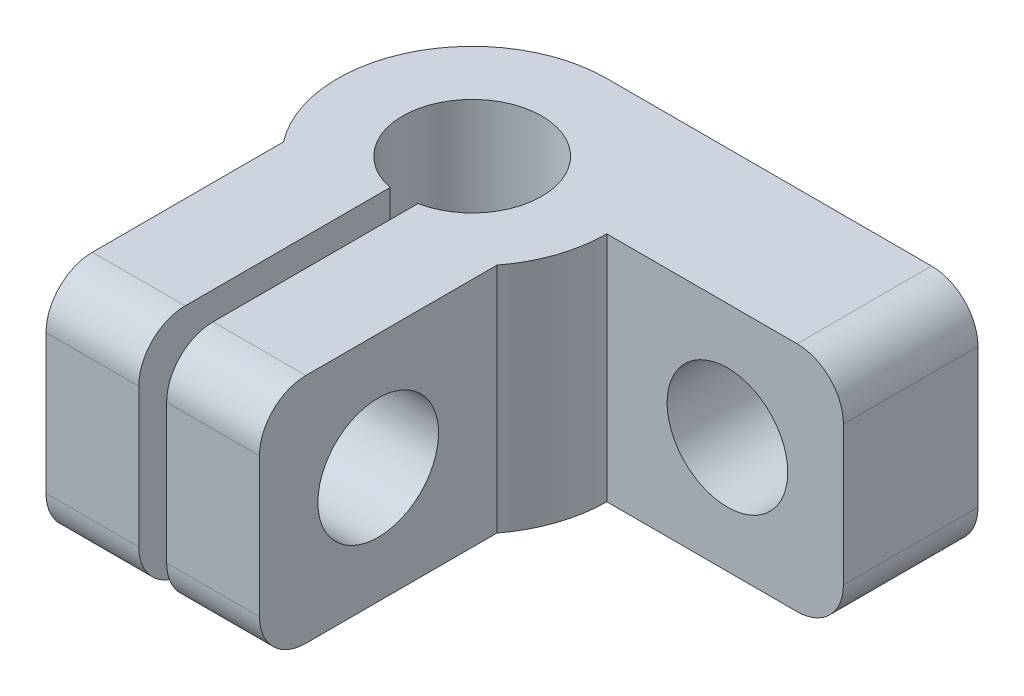
SolidWorks part; units mm, degrees
ref_plane "Front Plane" through (0, 0, 0) normal (0, 0, 1) x (1, 0, 0)
ref_plane "Top Plane" through (0, 0, 0) normal (0, 1, 0) x (1, 0, 0)
ref_plane "Right Plane" through (0, 0, 0) normal (1, 0, 0) x (0, 0, -1)
sketch "Sketch1" plane through (0, 0, 0) normal (0, 1, 0) x (1, 0, 0)
  line L0 (0, 2.9) -> (8, 2.9)
  line L1 (8, 2.9) -> (8, 0)
  line L2 (8, 0) -> (2.9, 0)
  line L3 (0, 0) -> (0, -2.9) construction
  line L4 (-0.3, -2.8844) -> (-0.3, -1.4697)
  line L5 (0.3, -2.8844) -> (0.3, -1.4697)
  line L6 (-0.3, -2.8844) -> (-0.3, -6.8844)
  line L7 (-0.3, -6.8844) -> (-2.3, -6.8844)
  line L8 (-2.3, -6.8844) -> (-2.3, -1.7664)
  line L9 (0.3, -2.8844) -> (0.3, -6.8844)
  line L10 (0.3, -6.8844) -> (2.3, -6.8844)
  line L11 (2.3, -6.8844) -> (2.3, -1.7664)
  arc A0 (0.3, -1.4697) -> (-0.3, -1.4697) centre (0, 0) ccw
  arc A1 (0, 2.9) -> (-2.3, -1.7664) centre (0, 0) ccw
  arc A2 (-0.3, -2.8844) -> (0.3, -2.8844) centre (0, 0) ccw
  arc A3 (2.3, -1.7664) -> (2.9, 0) centre (0, 0) ccw
  dimension "D1" = 3
  dimension "D2" = 5.8
  dimension "D7" = 4
  dimension "D3" = 0.3
  dimension "D4" = 0.3
  dimension "D5" = 2
  dimension "D6" = 2
  dimension "D8" = 4
  dimension "D9" = 8
  dimension "D10" = 2.9
extrude "Boss-Extrude1" add sketch "Sketch1" along normal blind 5 contours L11 A3 L2 L1 L0 A1 L8 L7 L6 L4 A0 L5 L9 L10
sketch "Sketch2" plane through (-2.3, 0, 0) normal (-1, 0, 0) x (0, 0, 1)
  line L0 (1.7664, 2.5) -> (6.8844, 2.5) construction
  line L1 (1.7664, 5) -> (1.7664, 0) construction
  line L2 (6.8844, 5) -> (6.8844, 0) construction
  circle A0 centre (4.3254, 2.5) radius 1.3
  dimension "D1" = 2.6
extrude "Cut-Extrude1" cut sketch "Sketch2" against normal through all
sketch "Sketch3" plane through (0, 0, -2.9) normal (0, 0, -1) x (-1, 0, 0)
  line L0 (-8, 2.5) -> (0, 2.5) construction
  line L1 (-8, 5) -> (-8, 0) construction
  line L2 (0, 5) -> (0, 0) construction
  circle A0 centre (-5.5, 2.5) radius 1.3
  dimension "D1" = 2.6
  dimension "D2" = 2.5
extrude "Cut-Extrude2" cut sketch "Sketch3" against normal through all
fillet "Fillet1" radius 1 4 edges at (-1.3, 5, 6.8844) (-1.3, 0, 6.8844) (1.3, 0, 6.8844) (1.3, 5, 6.8844)
fillet "Fillet2" radius 1 2 edges at (8, 0, -1.45) (8, 5, -1.45)
